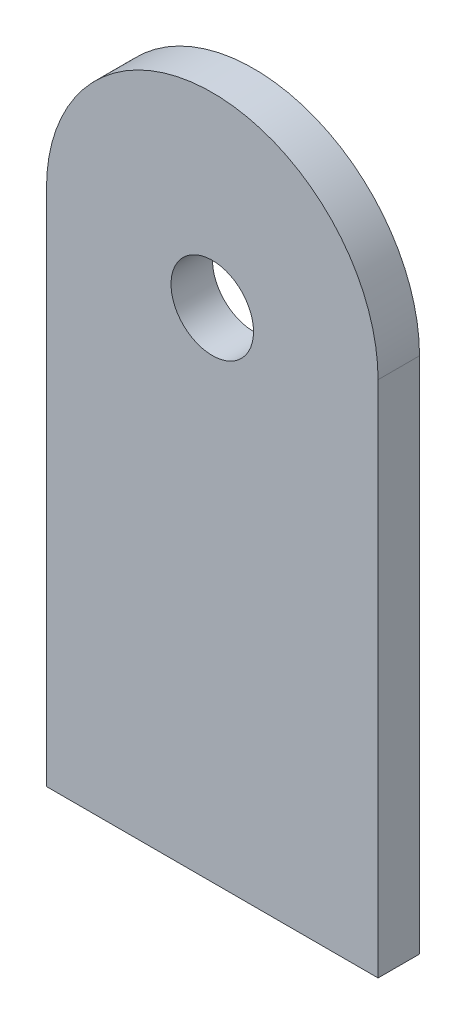
SolidWorks part; units mm, degrees
ref_plane "Front Plane" through (0, 0, 0) normal (0, 0, 1) x (1, 0, 0)
ref_plane "Top Plane" through (0, 0, 0) normal (0, 1, 0) x (1, 0, 0)
ref_plane "Right Plane" through (0, 0, 0) normal (1, 0, 0) x (0, 0, -1)
sketch "Sketch1" plane through (0, 0, 0) normal (0, 1, 0) x (1, 0, 0)
  line L1 (0, 0) -> (203.2, 0)
  line L2 (0, 0) -> (0, 25.4)
  line L3 (0, 25.4) -> (203.2, 25.4)
  line L4 (203.2, 0) -> (203.2, 25.4)
  dimension "D1" = 203.2
  dimension "D2" = 25.4
extrude "Boss-Extrude1" add sketch "Sketch1" along normal blind 609.6
sketch "Sketch2" plane through (0, 0, 0) normal (0, 0, 1) x (1, 0, 0)
  line L0 (101.6, 609.6) -> (101.6, 0) construction
  line L1 (0, 609.6) -> (203.2, 609.6) construction
  line L2 (0, 0) -> (203.2, 0) construction
  circle A0 centre (101.6, 304.8) radius 25.273
  dimension "D1" = 50.546
extrude "Cut-Extrude1" cut sketch "Sketch2" against normal through all
sketch "Sketch3" plane through (0, 0, -25.4) normal (0, 0, -1) x (-1, 0, 0)
  line L0 (-203.2, 317.5) -> (0, 317.5) construction
  line L1 (-203.2, 609.6) -> (-203.2, 0) construction
  line L2 (0, 609.6) -> (0, 0) construction
  line L3 (-203.2, 317.5) -> (-203.2, 609.6)
  line L4 (-203.2, 609.6) -> (0, 609.6)
  line L5 (0, 609.6) -> (0, 317.5)
  arc A0 (-203.2, 317.5) -> (0, 317.5) centre (-101.6, 317.5) cw
  circle A1 centre (-101.6, 304.8) radius 25.273 construction
  dimension "D1" = 12.7
extrude "Cut-Extrude2" cut sketch "Sketch3" against normal through all
